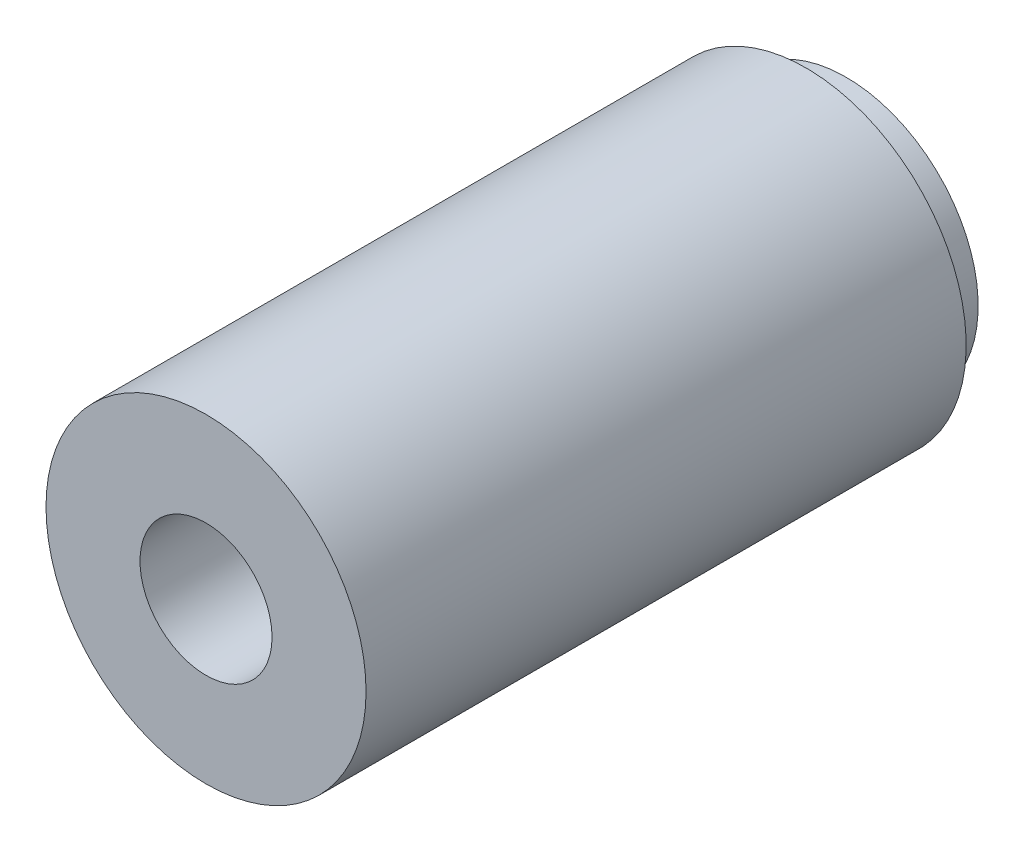
SolidWorks part; units mm, degrees
ref_plane "Plan de face" through (0, 0, 0) normal (0, 0, 1) x (1, 0, 0)
ref_plane "Plan de dessus" through (0, 0, 0) normal (0, 1, 0) x (1, 0, 0)
ref_plane "Plan de droite" through (0, 0, 0) normal (1, 0, 0) x (0, 0, -1)
sketch "Esquisse1" plane through (0, 0, 0) normal (0, 0, 1) x (1, 0, 0)
  circle A0 centre (0, 0) radius 4
  dimension "D1" = 8
extrude "Boss.-Extru.1" add sketch "Esquisse1" along normal blind 16
hole_wizard "Trou taraudé M41" positions "Esquisse2" profile "Esquisse3" tap size "M4" standard "ISO"
sketch "Esquisse2" plane through (0, 0, 16) normal (0, 0, 1) x (1, 0, 0)
  point P0 (0, 0)
sketch "Esquisse3" plane through (0, 0, 16) normal (1, 0, 0) x (0, -1, 0)
  line L0 (0, 0) -> (0, 8.9914)
  line L1 (0, 8.9914) -> (1.65, 8)
  line L2 (1.65, 8) -> (1.65, 0)
  line L5 (1.65, 0) -> (0, 0)
  line L10 (0, 8.9914) -> (-1.65, 8) construction
  line L11 (0, -6.35) -> (0, 107.95) construction
  dimension "Diamètre du trou pour taraudage" = 3.3
  dimension "Profondeur du trou pour taraudage" = 8
  dimension "Angle de pointe" = 118
cosmetic thread "Filetage de perçage1" parameters "D1"=8, "D2"=4
sketch "Esquisse4" plane through (0, 0, 0) normal (0, 0, -1) x (-1, 0, 0)
  circle A0 centre (0, 0) radius 2.5
  dimension "D1" = 5
extrude "Enlèv. mat.-Extru.1" cut sketch "Esquisse4" against normal blind 8
sketch "Esquisse5" plane through (0, 0, 0) normal (0, 0, -1) x (-1, 0, 0)
  circle A0 centre (0, 0) radius 3.3
  circle A1 centre (0, 0) radius 2.5 construction
  dimension "D1" = 0.8
extrude "Enlèv. mat.-Extru.2" cut sketch "Esquisse5" against normal blind 1 flip side to cut
